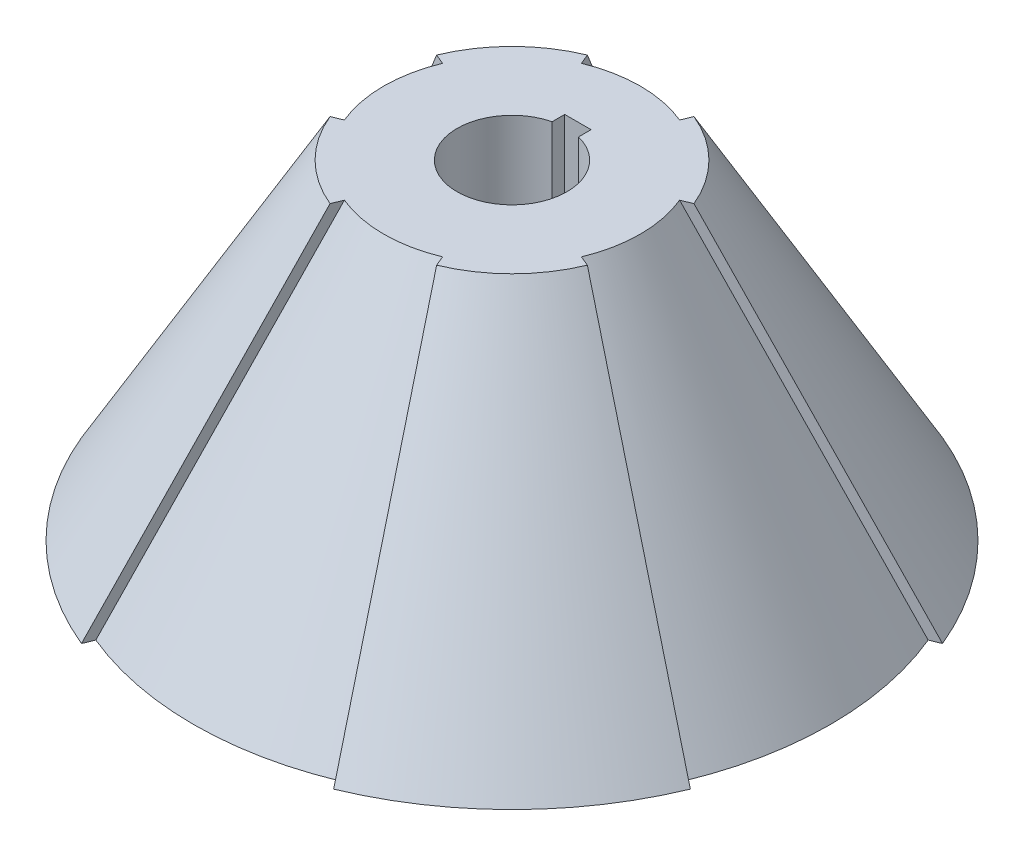
SolidWorks part; units mm, degrees
material "Ceramic Porcelain"
ref_plane "Front Plane" through (0, 0, 0) normal (0, 0, 1) x (1, 0, 0)
ref_plane "Top Plane" through (0, 0, 0) normal (0, 1, 0) x (1, 0, 0)
ref_plane "Right Plane" through (0, 0, 0) normal (1, 0, 0) x (0, 0, -1)
sketch "Sketch1" plane through (0, 0, 0) normal (0, 0, 1) x (1, 0, 0)
  line L0 (6.35, 0) -> (6.35, 38.1)
  line L1 (6.35, 38.1) -> (16.103, 38.1)
  line L2 (16.103, 38.1) -> (38.1, 0)
  line L3 (38.1, 0) -> (6.35, 0)
  line L4 (0, 0) -> (0, 60.6353) construction
  dimension "D1" = 38.1
  dimension "D2" = 38.1
  dimension "D3" = 6.35
  dimension "D4" = 120
revolve "Revolve1" add sketch "Sketch1" angle 360 about L4
sketch "Sketch2" plane through (0, 38.1, 0) normal (0, 1, 0) x (1, 0, 0)
  line L0 (-1.524, 7.62) -> (1.524, 7.62)
  line L1 (1.524, 7.62) -> (1.524, 6.1644)
  line L2 (-1.524, 7.62) -> (-1.524, 6.1644)
  circle A0 centre (0, 0) radius 6.35 construction
  point P2 (0, 7.62)
  dimension "D1" = 3.048
  dimension "D2" = 7.62
extrude "Cut-Extrude1" cut sketch "Sketch2" against normal through all and the other way through all
sketch "Sketch3" plane through (0, 0, 0) normal (1, 0, 0) x (0, 0, -1)
  line L0 (16.103, 38.1) -> (14.833, 38.1)
  line L1 (14.833, 38.1) -> (36.83, 0)
  line L2 (36.83, 0) -> (38.1, 0)
  line L3 (38.1, 0) -> (16.103, 38.1)
  line L4 (0, 0) -> (0, 56.8168) construction
  dimension "D1" = 1.27
revolve "Cut-Revolve1" cut sketch "Sketch3" angle 45 mid plane about L4
pattern_circular "CirPattern1" count 4 over 360 about axis through (0, 38.1, 0) along (0, -1, 0) of "Cut-Revolve1"
